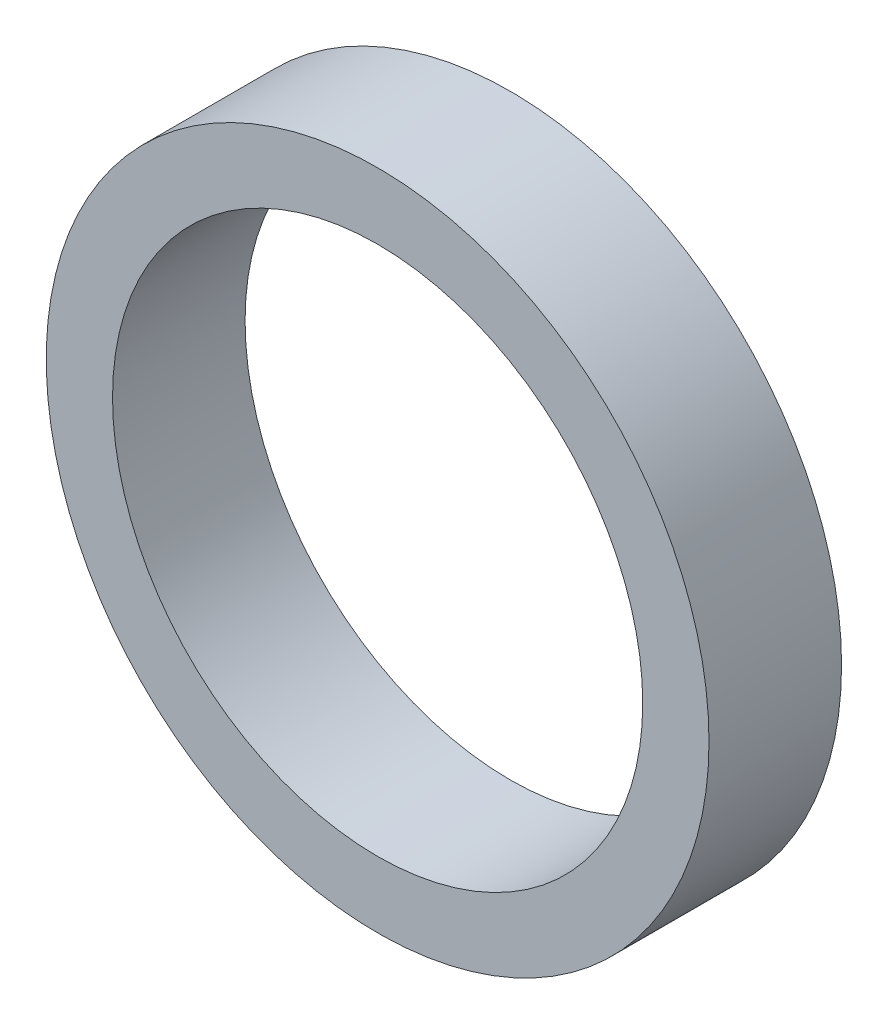
SolidWorks part; units mm, degrees
ref_plane "Front Plane" through (0, 0, 0) normal (0, 0, 1) x (1, 0, 0)
ref_plane "Top Plane" through (0, 0, 0) normal (0, 1, 0) x (1, 0, 0)
ref_plane "Right Plane" through (0, 0, 0) normal (1, 0, 0) x (0, 0, -1)
sketch "Sketch1" plane through (0, 0, 0) normal (0, 0, 1) x (1, 0, 0)
  circle A0 centre (0, 0) radius 10
  circle A1 centre (0, 0) radius 12.5
  dimension "D1" = 25
  dimension "D2" = 20
extrude "Boss-Extrude1" add sketch "Sketch1" along normal mid plane 5
